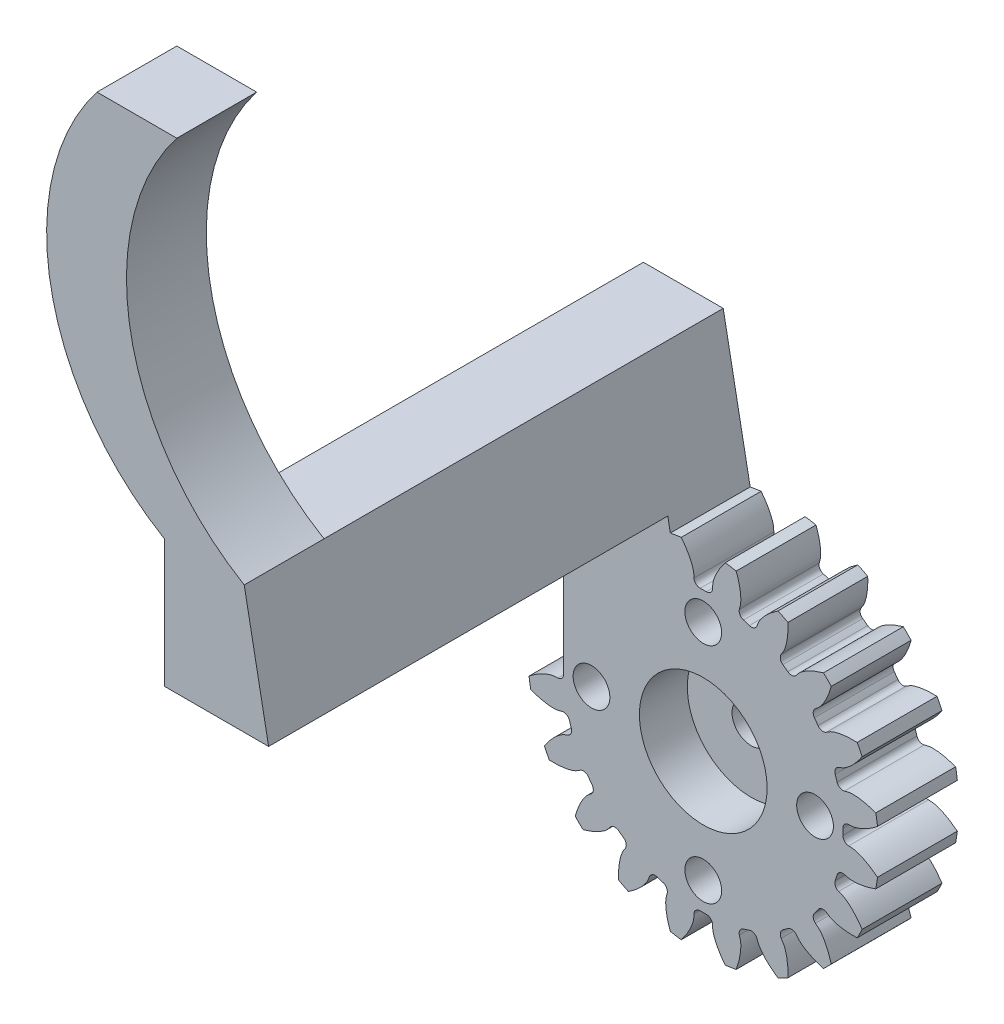
SolidWorks part; units mm, degrees
ref_plane "前视基准面" through (0, 0, 0) normal (0, 0, 1) x (1, 0, 0)
ref_plane "上视基准面" through (0, 0, 0) normal (0, 1, 0) x (1, 0, 0)
ref_plane "右视基准面" through (0, 0, 0) normal (1, 0, 0) x (0, 0, -1)
other "Configuration Table"
ref_axis "Axis1" through (0, 0, -88.99) along (0, 0, 1)
sketch "草图1" plane through (0, 0, 0) normal (0, 0, 1) x (1, 0, 0)
  circle A0 centre (0, 0) radius 11
extrude "LaShenA" add sketch "草图1" along normal blind 5
sketch "SketchA" plane through (0, 0, 5) normal (0, 0, 1) x (1, 0, 0)
  line L0 (0, 0) -> (0, 11) construction
  arc A0 (0.1927, 8.7479) -> (-0.1927, 8.7479) centre (0, 0) ccw
  arc A1 (1.7931, 11.3831) -> (-1.7931, 11.3831) centre (0, 0) ccw
  arc A2 (-0.1927, 8.7479) -> (-0.5803, 9.1044) centre (-0.201, 9.1278) cw
  arc A3 (0.5803, 9.1044) -> (0.1927, 8.7479) centre (0.201, 9.1278) cw
  circle A4 centre (0, 0) radius 9.3969 construction
  circle A5 centre (0, 0) radius 11 construction
  circle A6 centre (0, 0) radius 8.75 construction
  circle A7 centre (0, 0) radius 10 construction
  spline S0 degree 3 poles (0.5803, 9.1044) (0.586, 9.1962) (0.5881, 9.3163) (0.608, 9.4484) (0.6204, 9.5043) (0.6313, 9.5485) (0.6452, 9.5991) (0.6626, 9.656) (0.6838, 9.7191) (0.7091, 9.7882) (0.7388, 9.863) (0.7734, 9.9435) (0.813, 10.0293) (0.8581, 10.1203) (0.909, 10.2162) (0.9658, 10.3168) (1.0291, 10.4219) (1.0989, 10.531) (1.1756, 10.644) (1.2595, 10.7606) (1.3507, 10.8803) (1.4496, 11.0031) (1.5949, 11.1737) (1.7116, 11.2996) (1.7931, 11.3831) knots 0.125068 0.125068 0.125068 0.125068 0.215847 0.244833 0.257593 0.272674 0.290074 0.309794 0.331834 0.356194 0.382875 0.411875 0.443195 0.476835 0.512796 0.551076 0.591676 0.634597 0.679837 0.727398 0.777278 0.829478 0.883999 1 1 1 1
  spline S1 degree 3 poles (-0.5803, 9.1044) (-0.586, 9.1962) (-0.5881, 9.3163) (-0.608, 9.4484) (-0.6204, 9.5043) (-0.6313, 9.5485) (-0.6452, 9.5991) (-0.6626, 9.656) (-0.6838, 9.7191) (-0.7091, 9.7882) (-0.7388, 9.863) (-0.7734, 9.9435) (-0.813, 10.0293) (-0.8581, 10.1203) (-0.909, 10.2162) (-0.9658, 10.3168) (-1.0291, 10.4219) (-1.0989, 10.531) (-1.1756, 10.644) (-1.2595, 10.7606) (-1.3507, 10.8803) (-1.4496, 11.0031) (-1.5949, 11.1737) (-1.7116, 11.2996) (-1.7931, 11.3831) knots 0.125068 0.125068 0.125068 0.125068 0.215847 0.244833 0.257593 0.272674 0.290074 0.309794 0.331834 0.356194 0.382875 0.411875 0.443195 0.476835 0.512796 0.551076 0.591676 0.634597 0.679837 0.727398 0.777278 0.829478 0.883999 1 1 1 1
  dimension "D1" = 0.38
  dimension "Db" = 18.7939
  dimension "Da" = 22
  dimension "Df" = 17.5
  dimension "Dn" = 20
extrude "Cut-ExtrudeA" cut sketch "SketchA" against normal blind 30
pattern_circular "www.KYTool.cn" count 20 over 360 about axis through (0, 0, -88.99) along (0, 0, 1) of "Cut-ExtrudeA"
sketch "草图2" plane through (0, 0, 0) normal (0, 0, -1) x (-1, 0, 0)
  line L0 (0, 0) -> (-2.8865, 8.2602) construction
  line L1 (-2.8865, 8.2602) -> (-4.3877, 13.5541)
  line L2 (-4.3877, 13.5541) -> (-15.884, 0)
  line L3 (-15.884, 0) -> (0, 0)
  line L4 (-2.8865, 8.2602) -> (0, 0)
  circle A0 centre (0, 0) radius 8.75
  dimension "D1" = 17.5
extrude "切除-拉伸1" cut sketch "草图2" against normal blind 10 contours A0 L1 L2 L3
sketch "草图3" plane through (0, 0, 0) normal (0, 0, -1) x (-1, 0, 0)
  line L0 (0, 0) -> (-23.0545, 0) construction
  line L1 (0.0422, -0.2211) -> (-1.6181, 8.4783) construction
  line L2 (-2.0622, 10.805) -> (-3.75, 19.6487)
  line L3 (-8.75, 0) -> (-8.75, 19.6487)
  line L4 (-8.75, 19.6487) -> (-3.75, 19.6487)
  arc A1 (-2.52, 8.3793) -> (-8.7479, -0.1927) centre (0, 0) ccw construction
  arc A2 (-2.52, 8.3793) -> (-2.2615, 8.8382) centre (-2.6294, 8.7432) ccw construction
  arc A3 (-2.52, 8.3793) -> (-8.7479, -0.1927) centre (0, 0) ccw
  arc A4 (-2.52, 8.3793) -> (-2.2615, 8.8382) centre (-2.6294, 8.7432) ccw
  spline S0 degree 3 poles (-3888.1141, -935.3779) (183.6302, -1.8846) (6.4793, 35.2019) (-2.1274, 10.6231) (-2.1711, 10.4863) (-2.2092, 10.3552) (-2.2418, 10.2298) (-2.2695, 10.1104) (-2.2925, 9.9971) (-2.3112, 9.8902) (-2.326, 9.7897) (-2.3372, 9.6958) (-2.3452, 9.6086) (-2.3503, 9.5282) (-2.353, 9.4547) (-2.3537, 9.3882) (-2.3526, 9.3287) (-2.3503, 9.2762) (-2.347, 9.2308) (-2.3415, 9.1739) (-1.3146, 2.9927) (40.6951, 8.0893) (-3773.9722, -1322.6611) knots -25.433219 -25.433219 -25.433219 -25.433219 0.34779 0.397671 0.445231 0.490471 0.533392 0.573992 0.612273 0.648233 0.681873 0.713193 0.742194 0.768874 0.793234 0.815274 0.834995 0.852395 0.867475 0.880235 0.909221 7.081774 7.081774 7.081774 7.081774 only from (-2.0622, 10.805) to (-2.2615, 8.8382) construction
  spline S1 degree 3 poles (-2.0622, 10.805) (-2.085, 10.7439) (-2.1228, 10.6374) (-2.1711, 10.4863) (-2.2092, 10.3552) (-2.2418, 10.2298) (-2.2695, 10.1104) (-2.2925, 9.9971) (-2.3112, 9.8902) (-2.326, 9.7897) (-2.3372, 9.6958) (-2.3452, 9.6086) (-2.3503, 9.5282) (-2.353, 9.4547) (-2.3537, 9.3882) (-2.3526, 9.3287) (-2.3503, 9.2762) (-2.347, 9.2308) (-2.3415, 9.1739) (-2.3196, 9.0421) (-2.2845, 8.9271) (-2.2615, 8.8382) knots 0.332889 0.332889 0.332889 0.332889 0.397671 0.445231 0.490471 0.533392 0.573992 0.612273 0.648233 0.681873 0.713193 0.742194 0.768874 0.793234 0.815274 0.834995 0.852395 0.867475 0.880235 0.909221 1 1 1 1
  dimension "D1" = 5
extrude "凸台-拉伸1" add sketch "草图3" against normal blind 5 contours S1 L2 L4 L3 A3 A4
sketch "草图4" plane through (0, 0, 5) normal (0, 0, 1) x (1, 0, 0)
  line L0 (2.2232, 11.6487) -> (8.75, 11.6487)
  line L1 (2.0622, 10.805) -> (3.75, 19.6487) construction
  line L2 (8.75, 0) -> (8.75, 19.6487) construction
  line L3 (8.75, 11.6487) -> (8.75, 19.6487)
  line L4 (8.75, 19.6487) -> (3.75, 19.6487)
  line L5 (3.75, 19.6487) -> (2.2232, 11.6487)
  dimension "D1" = 8
extrude "凸台-拉伸2" add sketch "草图4" along normal blind 25
sketch "草图5" plane through (0, 19.6487, 0) normal (0, 1, 0) x (1, 0, 0)
  line L0 (3.75, -25) -> (8.75, -25)
  line L1 (3.75, -30) -> (3.75, 0) construction
  line L2 (8.75, -30) -> (8.75, 0) construction
  line L3 (8.75, -25) -> (8.75, -30)
  line L4 (8.75, -30) -> (3.75, -30)
  line L5 (3.75, -30) -> (3.75, -25)
  dimension "D1" = 5
sketch "草图6" plane through (0, 0, 30) normal (0, 0, 1) x (1, 0, 0)
  line L0 (2.2232, 11.6487) -> (3.7002, 19.3877) construction
  line L2 (3.75, 19.6487) -> (2.2232, 11.6487) construction
  line L3 (7.9714, 41.7675) -> (12.9714, 41.7675)
  line L4 (3.75, 19.6487) -> (8.75, 19.6487)
  arc A0 (3.75, 19.6487) -> (7.9714, 41.7675) centre (-3.8749, 32.5662) ccw
  arc A1 (8.75, 19.6487) -> (12.9714, 41.7675) centre (1.1251, 32.5662) ccw
  dimension "D1" = 15
  dimension "D2" = 15
  dimension "D3" = 5
  dimension "D4" = 5
extrude "凸台-拉伸4" add sketch "草图6" against normal blind 5
sketch "草图7" plane through (0, 0, 0) normal (0, 0, -1) x (-1, 0, 0)
  line L0 (0, 0) -> (0, 7) construction
  circle A0 centre (0, 0) radius 7 construction
  circle A1 centre (0, 7) radius 1.15
  circle A2 centre (7, 0) radius 1.15
  circle A3 centre (0, -7) radius 1.15
  circle A4 centre (-7, 0) radius 1.15
  point P14 (0, 0)
  dimension "D1" = 14
  dimension "D2" = 2.3
  dimension "D3" = 4
extrude "切除-拉伸2" cut sketch "草图7" against normal blind 5
sketch "草图8" plane through (0, 0, 0) normal (0, 0, -1) x (-1, 0, 0)
  circle A0 centre (0, 0) radius 4
  dimension "D1" = 8
extrude "切除-拉伸3" cut sketch "草图8" against normal blind 3 from offset 2 offset against normal yes
sketch "草图10" plane through (0, 0, 2) normal (0, 0, 1) x (1, 0, 0)
  circle A0 centre (0, 0) radius 1.2
  dimension "D1" = 2.4
extrude "切除-拉伸5" cut sketch "草图10" against normal blind 3
ref_plane "基准面1" through (-20, 0, 0) normal (1, 0, 0) x (0, 0, -1)
mirror "镜向2" about plane through (-20, 0, 0) normal (1, 0, 0) of bodies 119
delete or keep bodies "实体-删除/保留 1" bodies 119
sketch "草图11" plane through (0, 0, 0) normal (0, 0, -1) x (-1, 0, 0)
  circle A0 centre (40, 0) radius 10
  dimension "D1" = 20
